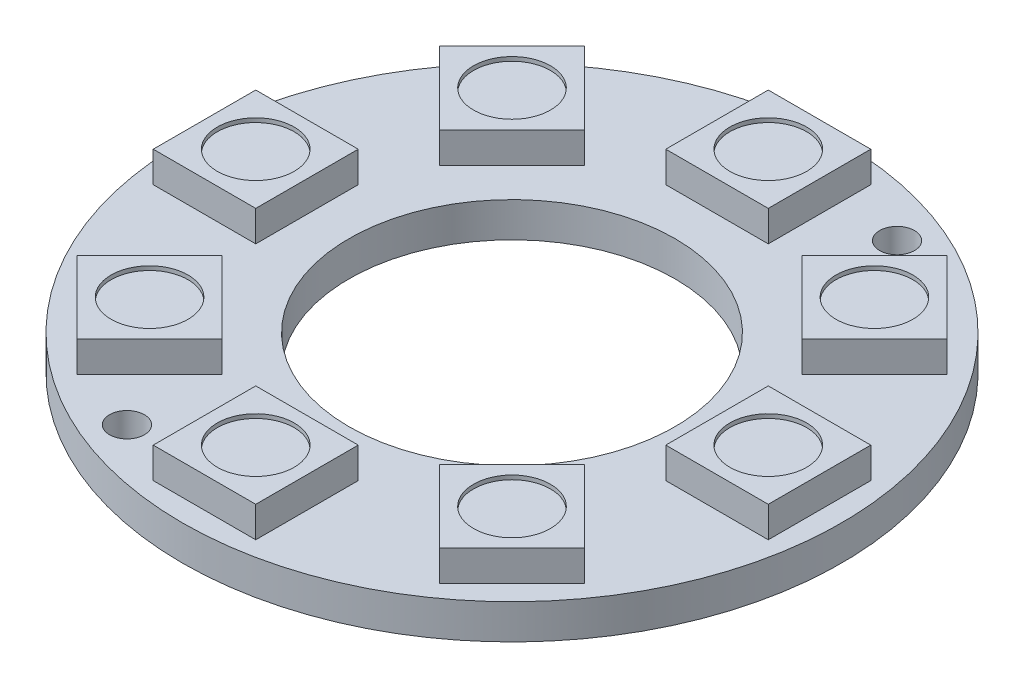
SolidWorks part; units mm, degrees
ref_plane "Plan de face" through (0, 0, 0) normal (0, 0, 1) x (1, 0, 0)
ref_plane "Plan de dessus" through (0, 0, 0) normal (0, 1, 0) x (1, 0, 0)
ref_plane "Plan de droite" through (0, 0, 0) normal (1, 0, 0) x (0, 0, -1)
sketch "Esquisse1" plane through (0, 0, 0) normal (0, 1, 0) x (1, 0, 0)
  line L0 (0, 0) -> (0, 16.075) construction
  line L1 (0, 0) -> (6.1516, 14.8514) construction
  line L2 (-7.3448, 3.0423) -> (0, 0) construction
  circle A0 centre (0, 0) radius 7.95
  circle A1 centre (0, 0) radius 16.075
  circle A2 centre (5.5011, 13.2808) radius 0.85
  circle A3 centre (-5.5011, -13.2808) radius 0.85
  dimension "D1" = 32.15
  dimension "D2" = 15.9
  dimension "D5" = 1.7
  dimension "D3" = 22.5
  dimension "D4" = 14.375
extrude "Boss.-Extru.1" add sketch "Esquisse1" along normal blind 1.7
sketch "Esquisse3" plane through (0, 0, 0) normal (0, -1, 0) x (1, 0, 0)
  line L0 (0, 0) -> (-16.075, 0) construction
  line L1 (-10.45, -5.5) -> (-13.45, -5.5)
  line L2 (-10.45, -5.5) -> (-10.45, -3.5)
  line L3 (-10.45, -3.5) -> (-13.45, -3.5)
  line L4 (-13.45, -5.5) -> (-13.45, -3.5)
  line L5 (-10.45, -5.5) -> (-10.45, 5.5) construction
  line L6 (-10.45, -2.5) -> (-13.45, -2.5)
  line L7 (-10.45, -2.5) -> (-10.45, -0.5)
  line L8 (-10.45, -0.5) -> (-13.45, -0.5)
  line L9 (-13.45, -2.5) -> (-13.45, -0.5)
  line L10 (-13.45, -5.5) -> (-13.45, 5.5) construction
  line L11 (-7.95, 0) -> (-7.95, -13.9715) construction
  line L12 (-13.45, 2.5) -> (-13.45, 0.5)
  line L13 (-10.45, 0.5) -> (-13.45, 0.5)
  line L14 (-10.45, 2.5) -> (-10.45, 0.5)
  line L15 (-10.45, 2.5) -> (-13.45, 2.5)
  line L16 (-13.45, 5.5) -> (-13.45, 3.5)
  line L17 (-10.45, 3.5) -> (-13.45, 3.5)
  line L18 (-10.45, 5.5) -> (-10.45, 3.5)
  line L19 (-10.45, 5.5) -> (-13.45, 5.5)
  circle A0 centre (0, 0) radius 16.075 construction
  circle A1 centre (0, 0) radius 7.95 construction
  point P23 (-13.45, 0)
  point P24 (-10.45, 0)
  dimension "D1" = 3
  dimension "D2" = 2
  dimension "D3" = 2
  dimension "D4" = 1
  dimension "D5" = 0.5
  dimension "D6" = 2.5
extrude "Boss.-Extru.2" add sketch "Esquisse3" along normal blind 0.1
sketch "Esquisse4" plane through (0, 1.7, 0) normal (0, 1, 0) x (1, 0, 0)
  line L0 (0, 0) -> (0, 16.075) construction
  line L2 (-2.5, 15) -> (2.5, 15)
  line L3 (-2.5, 15) -> (-2.5, 10)
  line L4 (-2.5, 10) -> (2.5, 10)
  line L5 (2.5, 15) -> (2.5, 10)
  circle A0 centre (0, 0) radius 16.075 construction
  dimension "D1" = 5
  dimension "D2" = 5
  dimension "D3" = 10
extrude "Boss.-Extru.3" add sketch "Esquisse4" along normal blind 1.5
sketch "Esquisse5" plane through (0, 3.2, 0) normal (0, 1, 0) x (1, 0, 0)
  line L0 (-2.5, 12.5) -> (2.5, 12.5) construction
  line L1 (-2.5, 15) -> (-2.5, 10) construction
  line L2 (2.5, 10) -> (2.5, 15) construction
  circle A0 centre (0, 12.5) radius 1.875
  dimension "D1" = 3.75
extrude "Enlèv. mat.-Extru.1" cut sketch "Esquisse5" against normal blind 0.2
pattern_circular "Répétition circulaire1" count 8 over 360 about axis through (0, 0, 0) along (0, 1, 0) of "Boss.-Extru.3", "Enlèv. mat.-Extru.1"
sketch "Esquisse6" plane through (0, 0, 0) normal (0, -1, 0) x (1, 0, 0)
  line L0 (-15.25, -5.1) -> (-13.45, -5.1) construction
  line L1 (-13.45, -3.5) -> (-13.45, -5.5) construction
  line L3 (-15.25, -5.1) -> (-15.25, 5.0836) construction
  line L4 (-13.45, -3.5) -> (-13.45, -5.5) construction
  line L5 (-13.45, -5.5) -> (-10.45, -5.5) construction
  line L6 (-13.45, -2.1) -> (-15.9372, -2.1) construction
  line L7 (-13.45, -0.5) -> (-13.45, -2.5) construction
  line L8 (-13.45, 0.9) -> (-16.0498, 0.9) construction
  line L9 (-13.45, 2.5) -> (-13.45, 0.5) construction
  line L10 (-13.45, 3.9) -> (-15.25, 3.9) construction
  line L11 (-13.45, 5.5) -> (-13.45, 3.5) construction
  circle A0 centre (0, 0) radius 16.075 construction
  text T0 "DI" font "Century Gothic" height in points 4
  text T1 "5V" font "Century Gothic" height in points 4
  text T2 "GND" font "Century Gothic" height in points 3
  text T3 "D0\r\n" font "Century Gothic" height in points 3
  dimension "D1" = 1.8
  dimension "D2" = 0.4
  dimension "D3" = 3
  dimension "D4" = 3
  dimension "D5" = 3
extrude "Boss.-Extru.4" add sketch "Esquisse6" along normal blind 0.1
